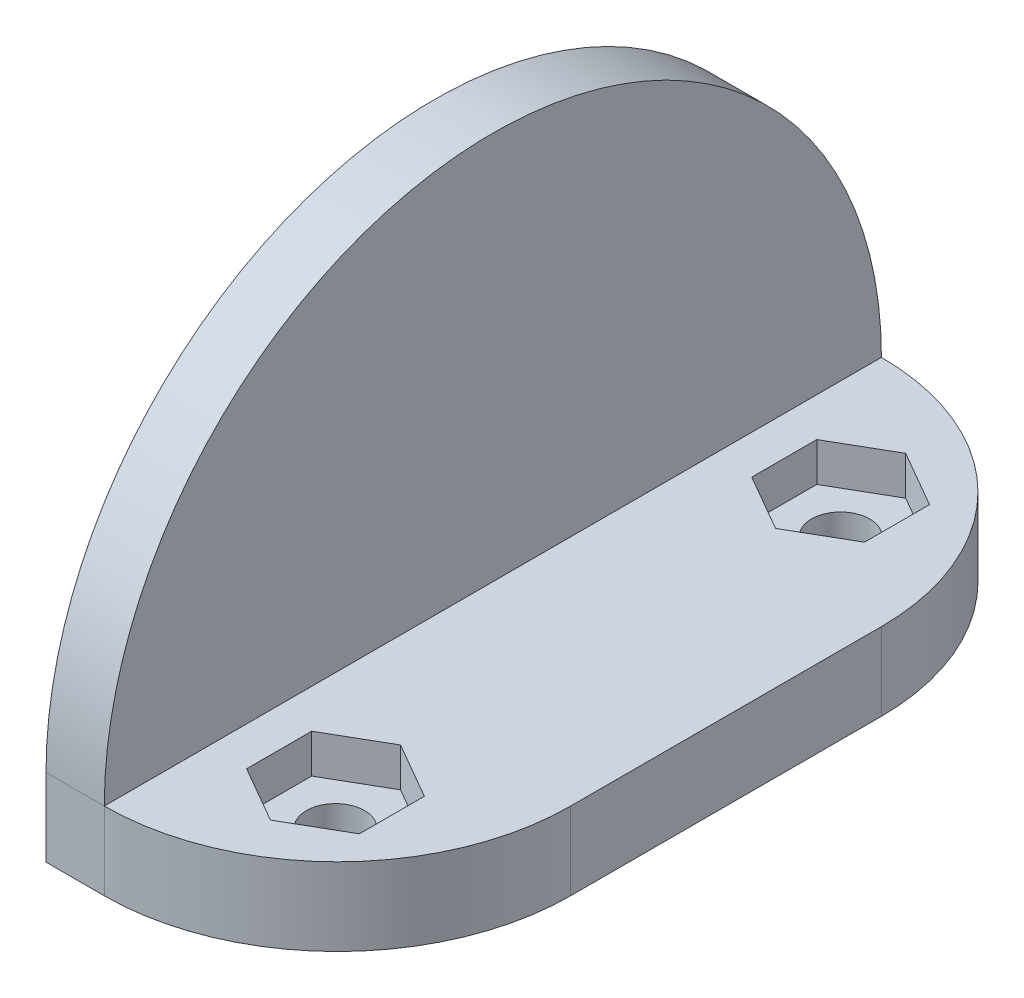
SolidWorks part; units mm, degrees
ref_plane "Alzado" through (0, 0, 0) normal (0, 0, 1) x (1, 0, 0)
ref_plane "Planta" through (0, 0, 0) normal (0, 1, 0) x (1, 0, 0)
ref_plane "Vista lateral" through (0, 0, 0) normal (1, 0, 0) x (0, 0, -1)
sketch "Croquis2" plane through (0, 0, 0) normal (0, 0, 1) x (1, 0, 0)
  line L0 (0, 26) -> (3, 26)
  line L1 (3, 26) -> (3, 4)
  line L2 (3, 4) -> (15, 4)
  line L3 (15, 4) -> (15, 0)
  line L4 (15, 0) -> (0, 0)
  line L5 (0, 0) -> (0, 26)
  dimension "D1" = 3
  dimension "D2" = 4
  dimension "D3" = 15
  dimension "D4" = 26
extrude "Saliente-Extruir1" add sketch "Croquis2" along normal blind 40
sketch "Croquis5" plane through (0, 4, 0) normal (0, 1, 0) x (1, 0, 0)
  line L0 (3, -40) -> (3, 0) construction
  line L1 (15, -40) -> (15, 0) construction
  line L2 (15, -12) -> (15, -28)
  line L4 (3, -40) -> (17.0084, -44.8122)
  line L5 (17.0084, -44.8122) -> (27.2068, -5.04)
  line L6 (27.2068, -5.04) -> (15.8727, 7.7552)
  line L7 (15.8727, 7.7552) -> (3, 0)
  arc A0 (3, 0) -> (15, -12) centre (3, -12) cw
  arc A1 (3, -40) -> (15, -28) centre (3, -28) ccw
sketch "Croquis6" plane through (3, 0, 0) normal (1, 0, 0) x (0, 0, -1)
  line L0 (-40, 4) -> (0, 4) construction
  line L3 (-40, 4) -> (-43.4632, 10.3059)
  line L4 (-43.4632, 10.3059) -> (-46.1031, 28.9908)
  line L5 (-46.1031, 28.9908) -> (-47.1867, 36.66)
  line L6 (-47.1867, 36.66) -> (8.7969, 26.4478)
  line L7 (8.7969, 26.4478) -> (6.3811, 12.0344)
  line L8 (6.3811, 12.0344) -> (0, 4)
  arc A0 (0, 4) -> (-40, 4) centre (-20, 4) ccw
extrude "Cortar-Extruir4" cut sketch "Croquis6" against normal blind 10
extrude "Cortar-Extruir5" cut sketch "Croquis5" against normal blind 10
sketch "Croquis7" plane through (0, 4, 0) normal (0, 1, 0) x (1, 0, 0)
  line L0 (3, -40) -> (3, 0) construction
  line L1 (7.9, -3.6514) -> (5, -5.3257)
  line L2 (5, -5.3257) -> (5, -8.6743)
  line L3 (5, -8.6743) -> (7.9, -10.3486)
  line L4 (7.9, -10.3486) -> (10.8, -8.6743)
  line L5 (10.8, -8.6743) -> (10.8, -5.3257)
  line L6 (10.8, -5.3257) -> (7.9, -3.6514)
  line L7 (5, -31.3257) -> (5, -34.6743)
  line L8 (5, -34.6743) -> (7.9, -36.3486)
  line L9 (7.9, -36.3486) -> (10.8, -34.6743)
  line L10 (10.8, -34.6743) -> (10.8, -31.3257)
  line L11 (10.8, -31.3257) -> (7.9, -29.6514)
  line L12 (7.9, -29.6514) -> (5, -31.3257)
  line L13 (7.9, -7) -> (3, 0) construction
  line L14 (3, -40) -> (7.9, -33) construction
  circle A0 centre (7.9, -7) radius 2.9 construction
  circle A1 centre (7.9, -33) radius 2.9 construction
  dimension "D1" = 5.8
  dimension "D2" = 26
  dimension "D3" = 2
  dimension "D4" = 2
extrude "Cortar-Extruir6" cut sketch "Croquis7" against normal blind 2
sketch "Croquis8" plane through (0, 2, 0) normal (0, 1, 0) x (1, 0, 0)
  line L0 (5, -5.3257) -> (7.9, -7) construction
  line L1 (7.9, -7) -> (5, -8.6743) construction
  line L2 (5, -5.3257) -> (5, -8.6743) construction
  circle A0 centre (7.9, -7) radius 1.5
  dimension "D1" = 3
extrude "Cortar-Extruir7" cut sketch "Croquis8" against normal blind 42
sketch "Croquis9" plane through (0, 2, 0) normal (0, 1, 0) x (1, 0, 0)
  line L0 (5, -31.3257) -> (7.9, -33) construction
  line L1 (7.9, -33) -> (5, -34.6743) construction
  line L2 (5, -31.3257) -> (5, -34.6743) construction
  circle A0 centre (7.9, -33) radius 1.5
  dimension "D1" = 3
extrude "Cortar-Extruir8" cut sketch "Croquis9" against normal blind 42
